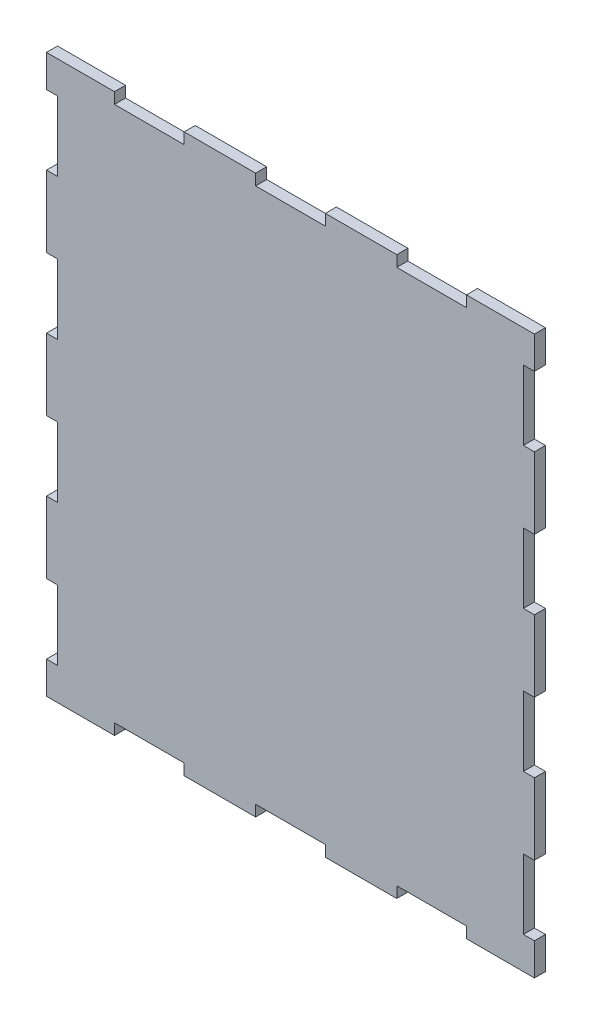
SolidWorks part; units mm, degrees
ref_plane "Front Plane" through (0, 0, 0) normal (0, 0, 1) x (1, 0, 0)
ref_plane "Top Plane" through (0, 0, 0) normal (0, 1, 0) x (1, 0, 0)
ref_plane "Right Plane" through (0, 0, 0) normal (1, 0, 0) x (0, 0, -1)
sketch "Sketch1" plane through (0, 0, 0) normal (0, 0, 1) x (1, 0, 0)
  line L1 (-75.9819, -25.5685) -> (64.0181, -25.5685)
  line L2 (-75.9819, -25.5685) -> (-75.9819, 134.4315)
  line L3 (-75.9819, 134.4315) -> (64.0181, 134.4315)
  line L4 (64.0181, -25.5685) -> (64.0181, 134.4315)
  dimension "D1" = 140
  dimension "D2" = 160
extrude "Boss-Extrude2" add sketch "Sketch1" along normal blind 3.175
sketch "Sketch3" plane through (0, 0, 3.175) normal (0, 0, 1) x (1, 0, 0)
  line L0 (-75.9819, 134.4315) -> (-75.9819, -25.5685) construction
  line L1 (-75.9819, -16.3185) -> (-72.8069, -16.3185)
  line L2 (-75.9819, -16.3185) -> (-75.9819, 3.6815)
  line L3 (-75.9819, 3.6815) -> (-72.8069, 3.6815)
  line L4 (-72.8069, -16.3185) -> (-72.8069, 3.6815)
  line L5 (-75.9819, -25.5685) -> (64.0181, -25.5685) construction
  line L6 (-75.9819, 24.1815) -> (-72.8069, 24.1815)
  line L7 (-75.9819, 24.1815) -> (-75.9819, 44.1815)
  line L8 (-75.9819, 44.1815) -> (-72.8069, 44.1815)
  line L9 (-72.8069, 24.1815) -> (-72.8069, 44.1815)
  line L10 (-75.9819, 64.6815) -> (-72.8069, 64.6815)
  line L11 (-75.9819, 64.6815) -> (-75.9819, 84.6815)
  line L12 (-75.9819, 84.6815) -> (-72.8069, 84.6815)
  line L13 (-72.8069, 64.6815) -> (-72.8069, 84.6815)
  line L14 (-75.9819, 105.1815) -> (-72.8069, 105.1815)
  line L15 (-75.9819, 105.1815) -> (-75.9819, 125.1815)
  line L16 (-75.9819, 125.1815) -> (-72.8069, 125.1815)
  line L17 (-72.8069, 105.1815) -> (-72.8069, 125.1815)
  line L18 (-75.9819, -16.3185) -> (-75.9819, 24.1815) construction
  line L19 (-15.9819, -25.5685) -> (4.0181, -25.5685)
  line L20 (-56.4819, -25.5685) -> (-36.4819, -25.5685)
  line L21 (-56.4819, -25.5685) -> (-56.4819, -22.3935)
  line L22 (-56.4819, -22.3935) -> (-36.4819, -22.3935)
  line L23 (-36.4819, -25.5685) -> (-36.4819, -22.3935)
  line L24 (-15.9819, -25.5685) -> (-15.9819, -22.3935)
  line L25 (-15.9819, -22.3935) -> (4.0181, -22.3935)
  line L26 (4.0181, -25.5685) -> (4.0181, -22.3935)
  line L27 (24.5181, -25.5685) -> (44.5181, -25.5685)
  line L28 (24.5181, -25.5685) -> (24.5181, -22.3935)
  line L29 (24.5181, -22.3935) -> (44.5181, -22.3935)
  line L30 (44.5181, -25.5685) -> (44.5181, -22.3935)
  line L31 (-56.4819, -25.5685) -> (-15.9819, -25.5685) construction
  line L32 (64.0181, 54.4315) -> (-75.9819, 54.4315) construction
  line L33 (64.0181, -25.5685) -> (64.0181, 134.4315) construction
  line L39 (-5.9819, 134.4315) -> (-5.9819, -25.5685) construction
  line L41 (64.0181, 134.4315) -> (-75.9819, 134.4315) construction
  line L43 (-36.4819, 134.4315) -> (-36.4819, 131.2565)
  line L44 (-56.4819, 131.2565) -> (-36.4819, 131.2565)
  line L45 (-56.4819, 134.4315) -> (-56.4819, 131.2565)
  line L46 (-56.4819, 134.4315) -> (-36.4819, 134.4315)
  line L47 (4.0181, 134.4315) -> (4.0181, 131.2565)
  line L48 (-15.9819, 131.2565) -> (4.0181, 131.2565)
  line L49 (-15.9819, 134.4315) -> (-15.9819, 131.2565)
  line L50 (-15.9819, 134.4315) -> (4.0181, 134.4315)
  line L51 (44.5181, 134.4315) -> (44.5181, 131.2565)
  line L52 (24.5181, 131.2565) -> (44.5181, 131.2565)
  line L53 (24.5181, 134.4315) -> (24.5181, 131.2565)
  line L54 (24.5181, 134.4315) -> (44.5181, 134.4315)
  line L55 (64.0181, -16.3185) -> (64.0181, 24.1815) construction
  line L56 (60.8431, 105.1815) -> (60.8431, 125.1815)
  line L57 (64.0181, 125.1815) -> (60.8431, 125.1815)
  line L58 (64.0181, 105.1815) -> (64.0181, 125.1815)
  line L59 (64.0181, 105.1815) -> (60.8431, 105.1815)
  line L60 (60.8431, 64.6815) -> (60.8431, 84.6815)
  line L61 (64.0181, 84.6815) -> (60.8431, 84.6815)
  line L62 (64.0181, 64.6815) -> (64.0181, 84.6815)
  line L63 (64.0181, 64.6815) -> (60.8431, 64.6815)
  line L64 (60.8431, 24.1815) -> (60.8431, 44.1815)
  line L65 (64.0181, 44.1815) -> (60.8431, 44.1815)
  line L66 (64.0181, 24.1815) -> (64.0181, 44.1815)
  line L67 (64.0181, 24.1815) -> (60.8431, 24.1815)
  line L68 (60.8431, -16.3185) -> (60.8431, 3.6815)
  line L69 (64.0181, 3.6815) -> (60.8431, 3.6815)
  line L70 (64.0181, -16.3185) -> (64.0181, 3.6815)
  line L71 (64.0181, -16.3185) -> (60.8431, -16.3185)
  dimension "D1" = 9.25
  dimension "D2" = 3.175
  dimension "D3" = 20
  dimension "D5" = 40.5
  dimension "D6" = 3.175
  dimension "D7" = 20
  dimension "D8" = 19.5
  dimension "D10" = 40.5
  dimension "D4" = 4
  dimension "D9" = 3
extrude "Cut-Extrude1" cut sketch "Sketch3" against normal up to next
